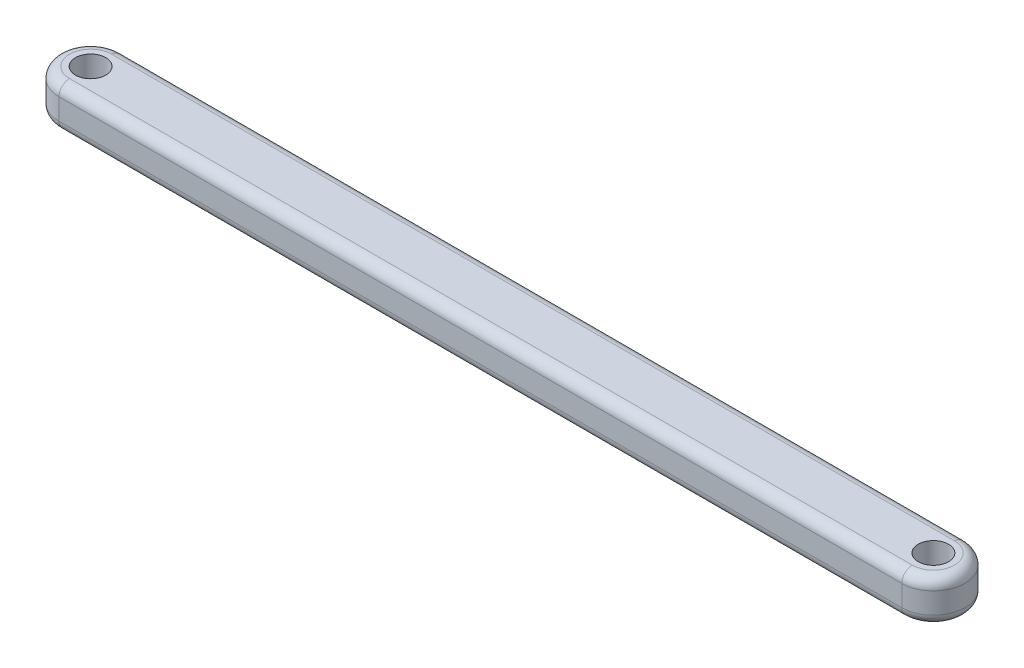
SolidWorks part; units mm, degrees
ref_plane "Front Plane" through (0, 0, 0) normal (0, 0, 1) x (1, 0, 0)
ref_plane "Top Plane" through (0, 0, 0) normal (0, 1, 0) x (1, 0, 0)
ref_plane "Right Plane" through (0, 0, 0) normal (1, 0, 0) x (0, 0, -1)
sketch "Sketch1" plane through (0, 0, 0) normal (0, 1, 0) x (1, 0, 0)
  line L0 (0, 0) -> (127, 0) construction
  line L1 (0, 4.7625) -> (127, 4.7625)
  line L2 (0, -4.7625) -> (127, -4.7625)
  arc A0 (0, 4.7625) -> (0, -4.7625) centre (0, 0) ccw
  arc A1 (127, -4.7625) -> (127, 4.7625) centre (127, 0) ccw
  point P3 (63.5, 0)
  dimension "D1" = 127
  dimension "D2" = 9.525
extrude "Boss-Extrude1" add sketch "Sketch1" along normal mid plane 6.35
sketch "Sketch2" plane through (0, 3.175, 0) normal (0, 1, 0) x (1, 0, 0)
  circle A0 centre (0, 0) radius 2.286
  circle A1 centre (127, 0) radius 2.286
  dimension "D1" = 4.572
extrude "Cut-Extrude1" cut sketch "Sketch2" against normal through all
fillet "Fillet1" radius 1.5875 8 edges at (131.7625, -3.175, 0) (63.5, -3.175, 4.7625) (-4.7625, -3.175, 0) (131.7625, 3.175, 0) (63.5, 3.175, 4.7625) (-4.7625, 3.175, 0) (63.5, -3.175, -4.7625) (63.5, 3.175, -4.7625)
